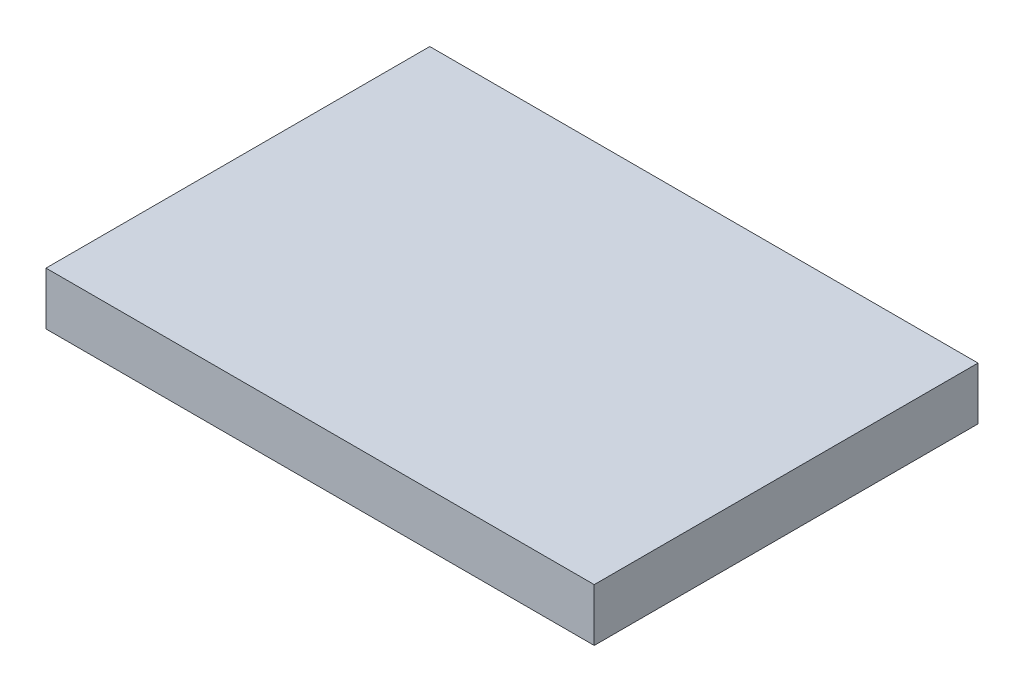
SolidWorks part; units mm, degrees
ref_plane "Front Plane" through (0, 0, 0) normal (0, 0, 1) x (1, 0, 0)
ref_plane "Top Plane" through (0, 0, 0) normal (0, 1, 0) x (1, 0, 0)
ref_plane "Right Plane" through (0, 0, 0) normal (1, 0, 0) x (0, 0, -1)
sketch "Sketch1" plane through (0, 0, 0) normal (0, 1, 0) x (1, 0, 0)
  line L1 (-16.51, 11.557) -> (16.51, 11.557)
  line L2 (-16.51, 11.557) -> (-16.51, -11.557)
  line L3 (-16.51, -11.557) -> (16.51, -11.557)
  line L4 (16.51, 11.557) -> (16.51, -11.557)
  line L5 (-16.51, 11.557) -> (16.51, -11.557) construction
  line L6 (-16.51, -11.557) -> (16.51, 11.557) construction
  point P0 (0, 0)
  dimension "D1" = 33.02
  dimension "D2" = 23.114
extrude "Boss-Extrude1" add sketch "Sketch1" along normal blind 3.175
